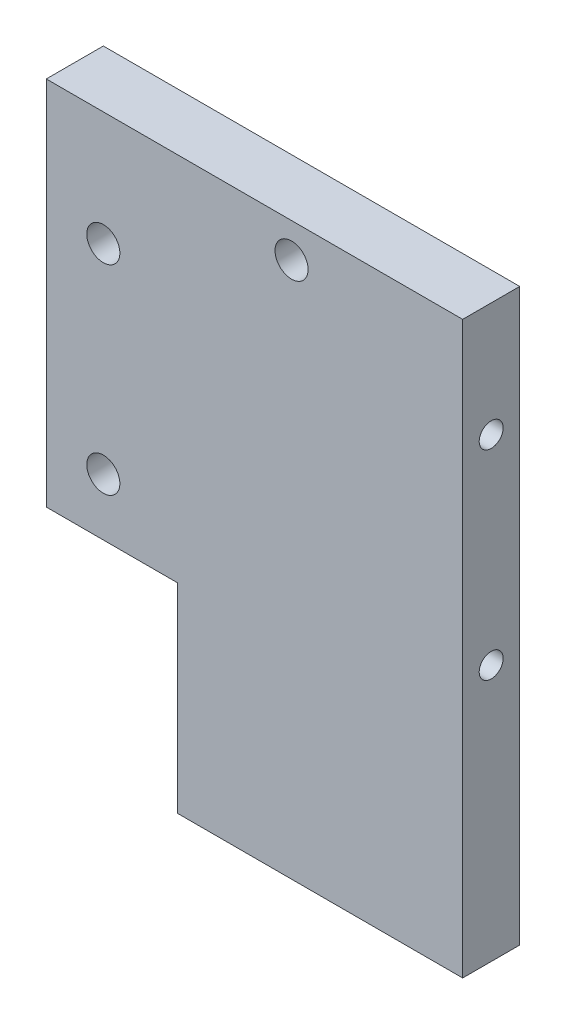
SolidWorks part; units mm, degrees
material "铝材"
ref_plane "前基準面" through (0, 0, 0) normal (0, 0, 1) x (1, 0, 0)
ref_plane "上基準面" through (0, 0, 0) normal (0, 1, 0) x (1, 0, 0)
ref_plane "右基準面" through (0, 0, 0) normal (1, 0, 0) x (0, 0, -1)
sketch "草图1" plane through (0, 0, 0) normal (0, 0, 1) x (1, 0, 0)
  line L1 (0, 0) -> (73, 0)
  line L2 (0, 0) -> (0, 100)
  line L3 (0, 100) -> (73, 100)
  line L4 (73, 0) -> (73, 100)
  dimension "D1" = 73
  dimension "D2" = 100
extrude "凸台-拉伸1" add sketch "草图1" along normal blind 10
hole_wizard "M5 六角凹头螺钉的柱形沉头孔1" positions "草图3" profile "草图2" counterbore size "M5" standard "ISO" end condition through all
sketch "草图3" plane through (0, 0, 0) normal (0, 0, -1) x (-1, 0, 0)
  line L0 (-73, 0) -> (-73, 100) construction
  line L1 (-73, 100) -> (0, 100) construction
  line L2 (0, 100) -> (0, 0) construction
  point P0 (-10, 80)
  point P1 (-43, 94)
  point P3 (-10, 45)
  dimension "D1" = 30
  dimension "D2" = 6
  dimension "D3" = 35
  dimension "D4" = 20
  dimension "D5" = 10
sketch "草图2" plane through (10, 80, 0) normal (1, 0, 0) x (0, 1, 0)
  line L0 (0, 0) -> (0, 10)
  line L1 (0, 10) -> (2.9, 10)
  line L3 (2.9, 10) -> (2.9, 5)
  line L4 (2.9, 5) -> (5, 5)
  line L5 (5, 5) -> (5, 0)
  line L7 (5, 0) -> (0, 0)
  line L11 (0, -6.35) -> (0, 107.95) construction
  dimension "通孔孔直径" = 5.8
  dimension "通孔孔深度" = 10
  dimension "柱形沉头孔直径" = 10
  dimension "柱形沉头孔深度" = 5
hole_wizard "M5 螺纹孔1" positions "草图5" profile "草图4" tap size "M5" standard "ISO"
sketch "草图5" plane through (73, 0, 0) normal (1, 0, 0) x (0, 0, -1)
  point P0 (-5, 80)
  point P1 (-5, 45)
sketch "草图4" plane through (73, 80, 5) normal (0, 1, 0) x (0, 0, -1)
  line L0 (0, 0) -> (0, 13.6618)
  line L1 (0, 13.6618) -> (2.1, 12.4)
  line L2 (2.1, 12.4) -> (2.1, 0)
  line L5 (2.1, 0) -> (0, 0)
  line L10 (0, 13.6618) -> (-2.1, 12.4) construction
  line L11 (0, -6.35) -> (0, 107.95) construction
  dimension "螺纹孔钻头直径" = 4.2
  dimension "螺纹孔钻头深度" = 12.4
  dimension "导头角度" = 118
cosmetic thread "孔螺蚊线1"
cosmetic thread "孔螺蚊线2"
sketch "草图6" plane through (0, 0, 0) normal (0, 0, -1) x (-1, 0, 0)
  line L1 (0, 0) -> (-23, 0)
  line L2 (0, 0) -> (0, 35)
  line L3 (0, 35) -> (-23, 35)
  line L4 (-23, 0) -> (-23, 35)
  dimension "D1" = 23
  dimension "D2" = 35
extrude "切除-拉伸1" cut sketch "草图6" against normal through all
